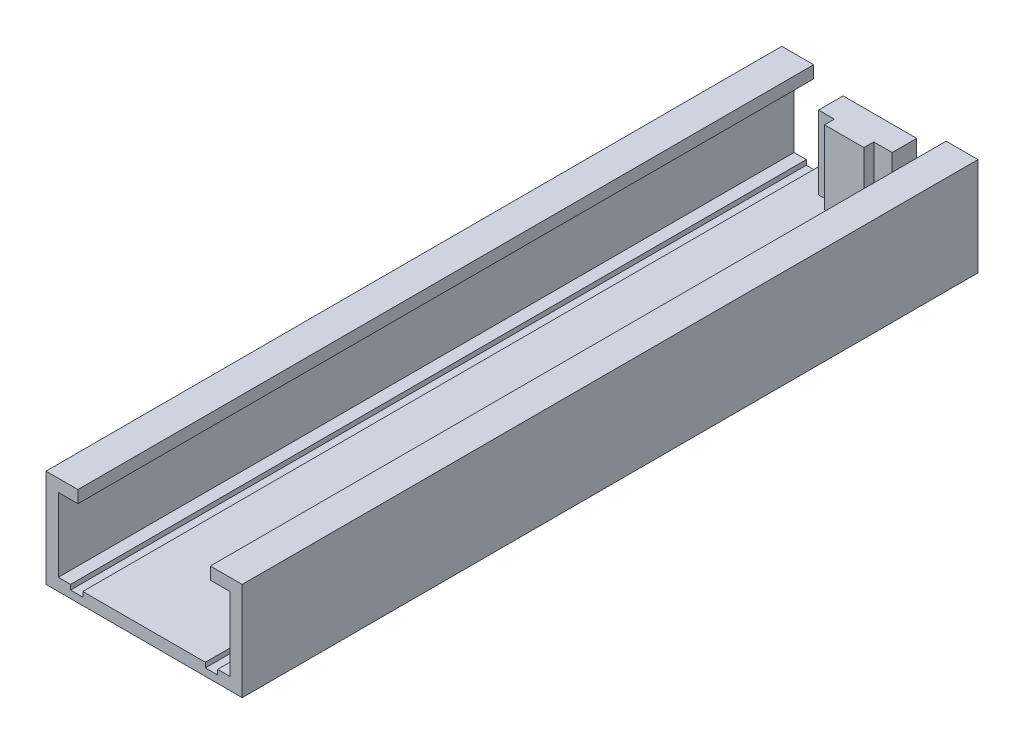
SolidWorks part; units mm, degrees
ref_plane "前基準面" through (0, 0, 0) normal (0, 0, 1) x (1, 0, 0)
ref_plane "上基準面" through (0, 0, 0) normal (0, 1, 0) x (1, 0, 0)
ref_plane "右基準面" through (0, 0, 0) normal (1, 0, 0) x (0, 0, -1)
sketch "草圖9" plane through (0, 0, 0) normal (0, 0, 1) x (1, 0, 0)
  line L1 (-4, 2) -> (4, 2)
  line L2 (-4, 2) -> (-4, -2)
  line L3 (-4, -2) -> (4, -2)
  line L4 (4, 2) -> (4, -2)
  line L5 (-4, 2) -> (4, -2) construction
  line L6 (-4, -2) -> (4, 2) construction
  point P0 (0, 0)
extrude "填料-伸長3" add sketch "草圖9" along normal blind 30 contours L3 L4 L1 L2
sketch "草圖10" plane through (0, 0, 0) normal (0, 0, -1) x (-1, 0, 0)
  line L0 (4, -2) -> (-4, -2) construction
  line L1 (-4, 2) -> (-3.5, 2)
  line L2 (-4, 2) -> (-4, -2)
  line L3 (-4, -2) -> (-3.5, -2)
  line L4 (-3.5, 2) -> (-3.5, -2)
sketch "草圖11" plane through (0, 0, 0) normal (0, 0, -1) x (-1, 0, 0)
  line L0 (-3.5, 2) -> (-3.5, -2) construction
  line L1 (4, -2) -> (-3.5, -2)
  line L2 (4, -2) -> (4, -1.5)
  line L3 (4, -1.5) -> (-3.5, -1.5)
  line L4 (-3.5, -2) -> (-3.5, -1.5)
sketch "草圖12" plane through (0, 0, 0) normal (0, 0, -1) x (-1, 0, 0)
  line L0 (4, -1.5) -> (-3.5, -1.5) construction
  line L1 (-3.5, 2) -> (3.5, 2)
  line L2 (-3.5, 2) -> (-3.5, -1.5)
  line L3 (-3.5, -1.5) -> (3.5, -1.5)
  line L4 (3.5, 2) -> (3.5, -1.5)
extrude "除料-伸長6" cut sketch "草圖12" against normal blind 30 contours L4 L3 L2 L1
sketch "草圖18" plane through (0, 0, 0) normal (0, 0, -1) x (-1, 0, 0)
  line L0 (4, -2) -> (-3.5, -2) construction
  line L1 (-3.5, -1.5) -> (-1.5, -1.5)
  line L2 (-3.5, -1.5) -> (-3.5, -2)
  line L3 (-3.5, -2) -> (-1.5, -2)
  line L4 (-1.5, -1.5) -> (-1.5, -2)
sketch "草圖19" plane through (0, -1.5, 0) normal (0, 1, 0) x (1, 0, 0)
  line L1 (1.5, 0) -> (-1.5, 0)
  line L2 (1.5, 0) -> (1.5, -1)
  line L3 (1.5, -1) -> (-1.5, -1)
  line L4 (-1.5, 0) -> (-1.5, -1)
extrude "填料-伸長5" add sketch "草圖19" along normal blind 3 contours L3 L4 L1 L2
sketch "草圖20" plane through (0, -1.5, 0) normal (0, 1, 0) x (1, 0, 0)
  line L0 (1.5, -1) -> (-1.5, -1) construction
  line L1 (0.7503, -1) -> (-0.8554, -1)
  line L2 (0.7503, -1) -> (0.7503, -1.4009)
  line L3 (0.7503, -1.4009) -> (-0.8554, -1.4009)
  line L4 (-0.8554, -1) -> (-0.8554, -1.4009)
extrude "填料-伸長6" add sketch "草圖20" along normal blind 3
sketch "草圖21" plane through (0, 0, 30) normal (0, 0, 1) x (1, 0, 0)
  line L0 (-4, -2) -> (4, -2) construction
  line L1 (-3.5, -1.5) -> (-3, -1.5)
  line L2 (-3.5, -1.5) -> (-3.5, -2)
  line L3 (-3.5, -2) -> (-3, -2)
  line L4 (-3, -1.5) -> (-3, -2)
sketch "草圖22" plane through (0, -1.5, 0) normal (0, 1, 0) x (1, 0, 0)
  line L0 (-4, 0) -> (3.5, 0) construction
  line L1 (-3, -30) -> (-2.5, -30)
  line L2 (-3, -30) -> (-3, 0)
  line L3 (-3, 0) -> (-2.5, 0)
  line L4 (-2.5, -30) -> (-2.5, 0)
extrude "除料-伸長7" cut sketch "草圖22" against normal blind 0.2 contours L4 L3 L2 L1
sketch "草圖23" plane through (0, 0, 30) normal (0, 0, 1) x (1, 0, 0)
  line L0 (-4, -2) -> (3.5, -2) construction
  line L1 (3.5, -1.5) -> (2.9973, -1.5)
  line L2 (3.5, -1.5) -> (3.5, -2)
  line L3 (3.5, -2) -> (2.9973, -2)
  line L4 (2.9973, -1.5) -> (2.9973, -2)
sketch "草圖24" plane through (0, -1.5, 0) normal (0, 1, 0) x (1, 0, 0)
  line L0 (-4, 0) -> (3.5, 0) construction
  line L1 (2.9973, -30) -> (2.4973, -30)
  line L2 (2.9973, -30) -> (2.9973, 0)
  line L3 (2.9973, 0) -> (2.4973, 0)
  line L4 (2.4973, -30) -> (2.4973, 0)
extrude "除料-伸長8" cut sketch "草圖24" against normal blind 0.2 contours L2 L3 L4 L1
sketch "草圖25" plane through (0, -1.5, 0) normal (0, 1, 0) x (1, 0, 0)
  circle A0 centre (0, -3.4706) radius 0.4576
extrude "除料-伸長9" cut sketch "草圖25" against normal blind 0.5 contours A0
sketch "草圖26" plane through (0, -1.5, 0) normal (0, 1, 0) x (1, 0, 0)
  ellipse E0 centre (0, -8.0523) end of major axis (0, -7.5558) minor radius 0.2464
extrude "除料-伸長10" cut sketch "草圖26" against normal blind 0.5
sketch "草圖27" plane through (0, -1.5, 0) normal (0, 1, 0) x (1, 0, 0)
  ellipse E0 centre (0, -9.4803) end of major axis (0, -9.1059) minor radius 0.2886
extrude "除料-伸長11" cut sketch "草圖27" against normal blind 0.5
sketch "草圖28" plane through (0, -1.5, 0) normal (0, 1, 0) x (1, 0, 0)
  line L1 (0.8691, -10.678) -> (0.5948, -10.678)
  line L2 (0.8691, -10.678) -> (0.8691, -6.6618)
  line L3 (0.8691, -6.6618) -> (0.5948, -6.6618)
  line L4 (0.5948, -10.678) -> (0.5948, -6.6618)
extrude "除料-伸長12" cut sketch "草圖28" against normal blind 0.5 contours L4 L3 L2 L1
sketch "草圖29" plane through (0, -1.5, 0) normal (0, 1, 0) x (1, 0, 0)
  line L1 (0.5948, -6.6618) -> (-0.643, -6.6618)
  line L2 (0.5948, -6.6618) -> (0.5948, -6.9618)
  line L3 (0.5948, -6.9618) -> (-0.643, -6.9618)
  line L4 (-0.643, -6.6618) -> (-0.643, -6.9618)
extrude "除料-伸長13" cut sketch "草圖29" against normal blind 0.5
sketch "草圖31" plane through (0, -1.5, 0) normal (0, 1, 0) x (1, 0, 0)
  line L0 (-0.643, -6.9618) -> (0.5948, -6.9618) construction
  line L1 (-0.357, -6.9618) -> (-0.643, -6.9618)
  line L2 (-0.357, -6.9618) -> (-0.357, -10.7737)
  line L3 (-0.357, -10.7737) -> (-0.643, -10.7737)
  line L4 (-0.643, -6.9618) -> (-0.643, -10.7737)
extrude "除料-伸長14" cut sketch "草圖31" against normal blind 0.5
sketch "草圖32" plane through (0, 0, 0) normal (0, 0, -1) x (-1, 0, 0)
  line L1 (-3.5, 2) -> (-2.7, 2)
  line L2 (-3.5, 2) -> (-3.5, 1.5)
  line L3 (-3.5, 1.5) -> (-2.7, 1.5)
  line L4 (-2.7, 2) -> (-2.7, 1.5)
  point P5 (0, 0)
extrude "填料-伸長7" add sketch "草圖32" against normal blind 30 contours L4 L3 L2 L1
sketch "草圖33" plane through (0, 0, 0) normal (0, 0, -1) x (-1, 0, 0)
  line L1 (3.5, 2) -> (2.7, 2)
  line L2 (3.5, 2) -> (3.5, 1.5)
  line L3 (3.5, 1.5) -> (2.7, 1.5)
  line L4 (2.7, 2) -> (2.7, 1.5)
extrude "填料-伸長8" add sketch "草圖33" against normal blind 30 contours L3 L4 L1 L2
